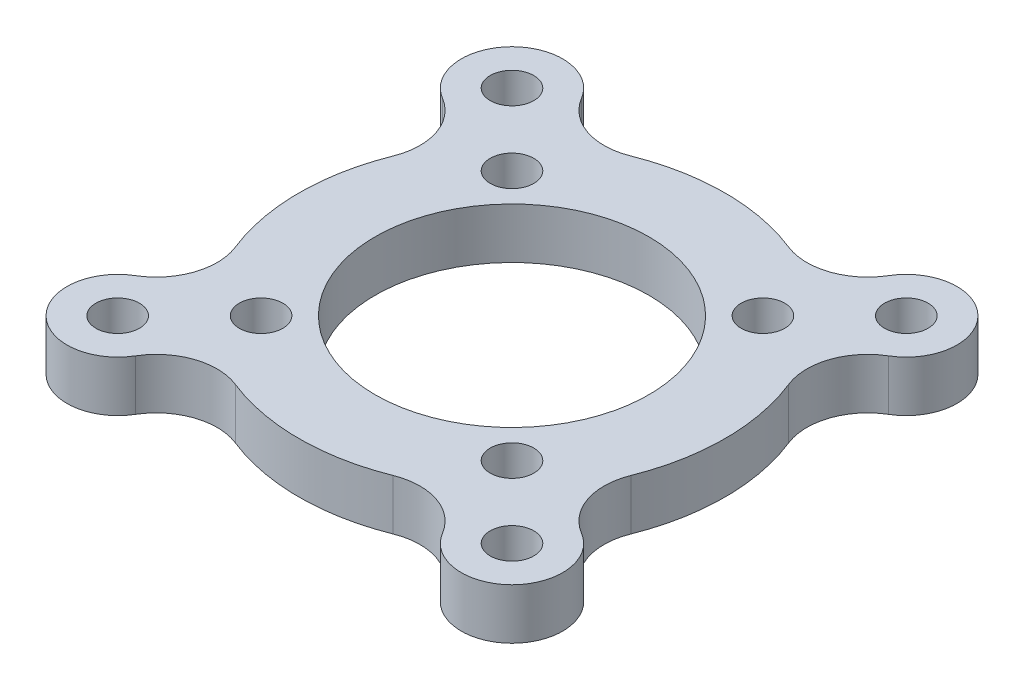
SolidWorks part; units mm, degrees
material "5052-H34"
ref_plane "正面" through (0, 0, 0) normal (0, 0, 1) x (1, 0, 0)
ref_plane "平面" through (0, 0, 0) normal (0, 1, 0) x (1, 0, 0)
ref_plane "右側面" through (0, 0, 0) normal (1, 0, 0) x (0, 0, -1)
sketch "ｽｹｯﾁ1" plane through (0, 0, 0) normal (0, 1, 0) x (1, 0, 0)
  line L0 (19.4454, 19.4454) -> (0, 0) construction
  line L4 (0, 0) -> (13.5, 0) construction
  line L5 (0, 0) -> (12.3744, 12.3744) construction
  circle A4 centre (0, 0) radius 13.5
  circle A5 centre (12.3744, 12.3744) radius 2.15
  circle A6 centre (12.3744, -12.3744) radius 2.15
  circle A7 centre (-12.3744, -12.3744) radius 2.15
  circle A8 centre (-12.3744, 12.3744) radius 2.15
  circle A9 centre (19.4454, 19.4454) radius 2.15
  arc A13 (19.5071, -7.7766) -> (19.5071, 7.7766) centre (0, 0) ccw
  arc A14 (22.0068, 15.1513) -> (15.1513, 22.0068) centre (19.4454, 19.4454) ccw
  arc A18 (15.1513, 22.0068) -> (7.7766, 19.5071) centre (9.9984, 25.0805) cw
  arc A19 (22.0068, 15.1513) -> (19.5071, 7.7766) centre (25.0805, 9.9984) ccw
  arc A20 (15.1513, -22.0068) -> (22.0068, -15.1513) centre (19.4454, -19.4454) ccw
  arc A21 (15.1513, -22.0068) -> (7.7766, -19.5071) centre (9.9984, -25.0805) ccw
  circle A22 centre (19.4454, -19.4454) radius 2.15
  arc A23 (22.0068, -15.1513) -> (19.5071, -7.7766) centre (25.0805, -9.9984) cw
  arc A24 (-22.0068, -15.1513) -> (-15.1513, -22.0068) centre (-19.4454, -19.4454) ccw
  arc A25 (-22.0068, -15.1513) -> (-19.5071, -7.7766) centre (-25.0805, -9.9984) ccw
  circle A26 centre (-19.4454, -19.4454) radius 2.15
  arc A27 (-15.1513, -22.0068) -> (-7.7766, -19.5071) centre (-9.9984, -25.0805) cw
  arc A28 (-15.1513, 22.0068) -> (-22.0068, 15.1513) centre (-19.4454, 19.4454) ccw
  arc A29 (-15.1513, 22.0068) -> (-7.7766, 19.5071) centre (-9.9984, 25.0805) ccw
  circle A30 centre (-19.4454, 19.4454) radius 2.15
  arc A31 (-22.0068, 15.1513) -> (-19.5071, 7.7766) centre (-25.0805, 9.9984) cw
  arc A32 (-7.7766, -19.5071) -> (7.7766, -19.5071) centre (0, 0) ccw
  arc A33 (7.7766, 19.5071) -> (-7.7766, 19.5071) centre (0, 0) ccw
  arc A34 (-19.5071, 7.7766) -> (-19.5071, -7.7766) centre (0, 0) ccw
  point P17 (0, 0)
  point P24 (0, 0)
  point P33 (0, 0)
  dimension "D2" = 10
  dimension "D4" = 27.5
  dimension "D6" = 27
  dimension "D8" = 4.3
  dimension "D3" = 4.3
  dimension "D12" = 42
  dimension "D14" = 6
  dimension "D7" = 45
  dimension "D9" = 17.5
  dimension "D11" = 45
  dimension "D10" = 4
extrude "ﾎﾞｽ - 押し出し1" add sketch "ｽｹｯﾁ1" along normal blind 5
